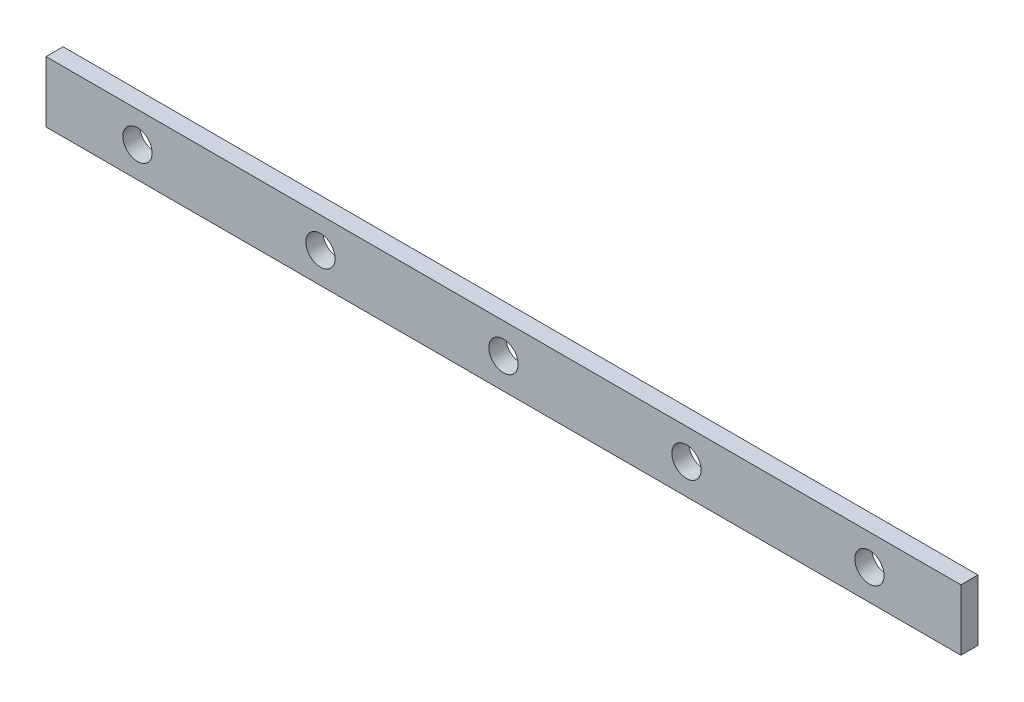
SolidWorks part; units mm, degrees
material "ABS"
ref_plane "前视基准面" through (0, 0, 0) normal (0, 0, 1) x (1, 0, 0)
ref_plane "上视基准面" through (0, 0, 0) normal (0, 1, 0) x (1, 0, 0)
ref_plane "右视基准面" through (0, 0, 0) normal (1, 0, 0) x (0, 0, -1)
other "Configuration Table"
sketch "草图1" plane through (0, 0, 0) normal (0, 0, 1) x (1, 0, 0)
  line L1 (-37.5, -2.5) -> (37.5, -2.5)
  line L2 (-37.5, -2.5) -> (-37.5, 2.5)
  line L3 (-37.5, 2.5) -> (37.5, 2.5)
  line L4 (37.5, -2.5) -> (37.5, 2.5)
  line L5 (-37.5, -2.5) -> (37.5, 2.5) construction
  line L6 (-37.5, 2.5) -> (37.5, -2.5) construction
  point P0 (0, 0)
  dimension "D1" = 5
  dimension "D2" = 75
extrude "凸台-拉伸1" add sketch "草图1" along normal blind 1.4
sketch "草图2" plane through (0, 0, 1.4) normal (0, 0, 1) x (1, 0, 0)
  circle A1 centre (30, 0) radius 1.025
  circle A2 centre (30, 0) radius 1.025 construction
  circle A3 centre (15, 0) radius 1.025
  circle A4 centre (15, 0) radius 1.025 construction
  circle A5 centre (0, 0) radius 1.025
  circle A6 centre (0, 0) radius 1.025 construction
  circle A7 centre (-15, 0) radius 1.025
  circle A8 centre (-15, 0) radius 1.025 construction
  circle A9 centre (-30, 0) radius 1.025
  circle A10 centre (-30, 0) radius 1.025 construction
  circle A15 centre (-30, 0) radius 1.2
  circle A16 centre (-15, 0) radius 1.2
  circle A17 centre (0, 0) radius 1.2
  circle A18 centre (15, 0) radius 1.2
  circle A19 centre (30, 0) radius 1.2
  dimension "D6" = 2.4
  dimension "D1" = 0
  dimension "D2" = 0
  dimension "D3" = 0
  dimension "D4" = 0
  dimension "D5" = 0
extrude "切除-拉伸1" cut sketch "草图2" against normal blind 51.4
